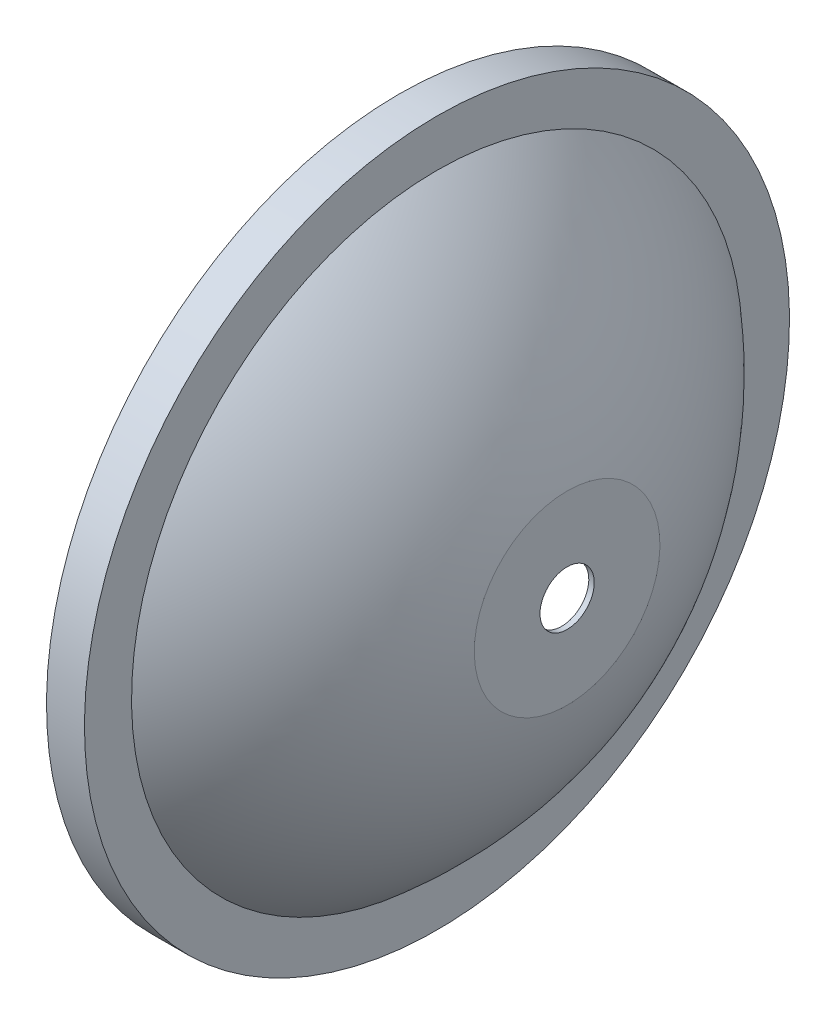
SolidWorks part; units mm, degrees
ref_plane "Front Plane" through (0, 0, 0) normal (0, 0, 1) x (1, 0, 0)
ref_plane "Top Plane" through (0, 0, 0) normal (0, 1, 0) x (1, 0, 0)
ref_plane "Right Plane" through (0, 0, 0) normal (1, 0, 0) x (0, 0, -1)
sketch "Sketch1" plane through (0, 0, 0) normal (0, 0, 1) x (1, 0, 0)
  line L0 (36.0177, 0) -> (-70.993, 0) construction
  line L1 (0, 5) -> (0, 17)
  line L2 (-23.993, 55.857) -> (-23.993, 64)
  line L3 (-23.993, 64) -> (-29.993, 64)
  line L4 (1, 5) -> (1, 17.1177)
  line L5 (-22.993, 56.3205) -> (-22.993, 65)
  line L6 (-22.993, 65) -> (-29.993, 65)
  line L7 (-29.993, 65) -> (-29.993, 64)
  line L8 (0, 5) -> (1, 5)
  arc A0 (-23.993, 55.857) -> (0, 17) centre (-70.993, 0) cw
  arc A1 (-22.993, 56.3205) -> (1, 17.1177) centre (-70.993, 0) cw
  dimension "D6" = 73
  dimension "D1" = 5
  dimension "D2" = 12
  dimension "D3" = 64
  dimension "D4" = 6
  dimension "D5" = 41
  dimension "D7" = 1
revolve "Revolve1" add sketch "Sketch1" angle 360 about L0
